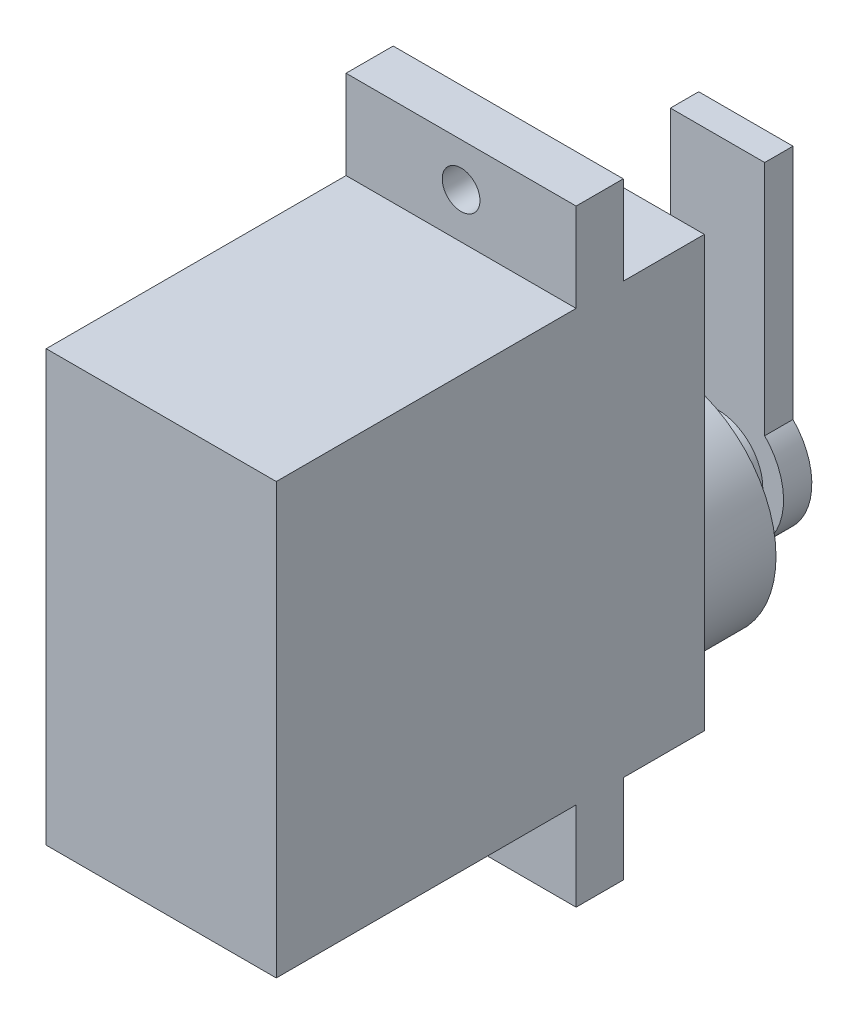
SolidWorks part; units mm, degrees
ref_plane "Alzado" through (0, 0, 0) normal (0, 0, 1) x (1, 0, 0)
ref_plane "Planta" through (0, 0, 0) normal (0, 1, 0) x (1, 0, 0)
ref_plane "Vista lateral" through (0, 0, 0) normal (1, 0, 0) x (0, 0, -1)
ref_plane "Plano1" through (0, 0, -4.3) normal (0, 0, 1) x (1, 0, 0)
sketch "Croquis1" plane through (0, 0, -4.3) normal (0, 0, 1) x (1, 0, 0)
  line L0 (-6.1, -5.9) -> (6.1, -5.9)
  line L1 (6.1, -5.9) -> (6.1, 16.9)
  line L2 (6.1, 16.9) -> (-6.1, 16.9)
  line L3 (-6.1, 16.9) -> (-6.1, -5.9)
extrude "Saliente-Extruir1" add sketch "Croquis1" along normal blind 22.7
sketch "Croquis2" plane through (0, 0, 0) normal (0, 0, 1) x (1, 0, 0)
  line L0 (-6.1, -10.6) -> (6.1, -10.6)
  line L1 (6.1, -10.6) -> (6.1, 21.6)
  line L2 (6.1, 21.6) -> (-6.1, 21.6)
  line L3 (-6.1, 21.6) -> (-6.1, -10.6)
extrude "Saliente-Extruir2" add sketch "Croquis2" along normal blind 2.5
ref_plane "Plano2" through (0, 0, -1) normal (0, 0, 1) x (1, 0, 0)
sketch "Croquis3" plane through (0, 0, -1) normal (0, 0, 1) x (1, 0, 0)
  circle A0 centre (0, -8.3) radius 1
  circle A1 centre (0, 19.3) radius 1
extrude "Cortar-Extruir1" cut sketch "Croquis3" along normal blind 4.5
ref_plane "Plano3" through (0, 0, -8.3) normal (0, 0, 1) x (1, 0, 0)
sketch "Croquis4" plane through (0, 0, -8.3) normal (0, 0, 1) x (1, 0, 0)
  circle A0 centre (0, 0) radius 5.9
extrude "Saliente-Extruir3" add sketch "Croquis4" along normal blind 4
ref_plane "Plano4" through (0, 0, -11.1) normal (0, 0, 1) x (1, 0, 0)
sketch "Croquis5" plane through (0, 0, -11.1) normal (0, 0, 1) x (1, 0, 0)
  circle A0 centre (0, 0) radius 2.4
extrude "Saliente-Extruir4" add sketch "Croquis5" along normal blind 2.8
ref_plane "Plano5" through (0, 0, -12.6) normal (0, 0, 1) x (1, 0, 0)
sketch "Croquis6" plane through (0, 0, -12.6) normal (0, 0, 1) x (1, 0, 0)
  circle A0 centre (0, 0) radius 3.5
extrude "Saliente-Extruir5" add sketch "Croquis6" along normal blind 1.5
ref_plane "Plano6" through (0, 0, -12.6) normal (0, 0, 1) x (1, 0, 0)
sketch "Croquis7" plane through (0, 0, -12.6) normal (0, 0, 1) x (1, 0, 0)
  line L0 (-2.5, 2) -> (2.5, 2)
  line L1 (2.5, 2) -> (2.5, 15)
  line L2 (2.5, 15) -> (-2.5, 15)
  line L3 (-2.5, 15) -> (-2.5, 2)
extrude "Saliente-Extruir6" add sketch "Croquis7" along normal blind 1.5
